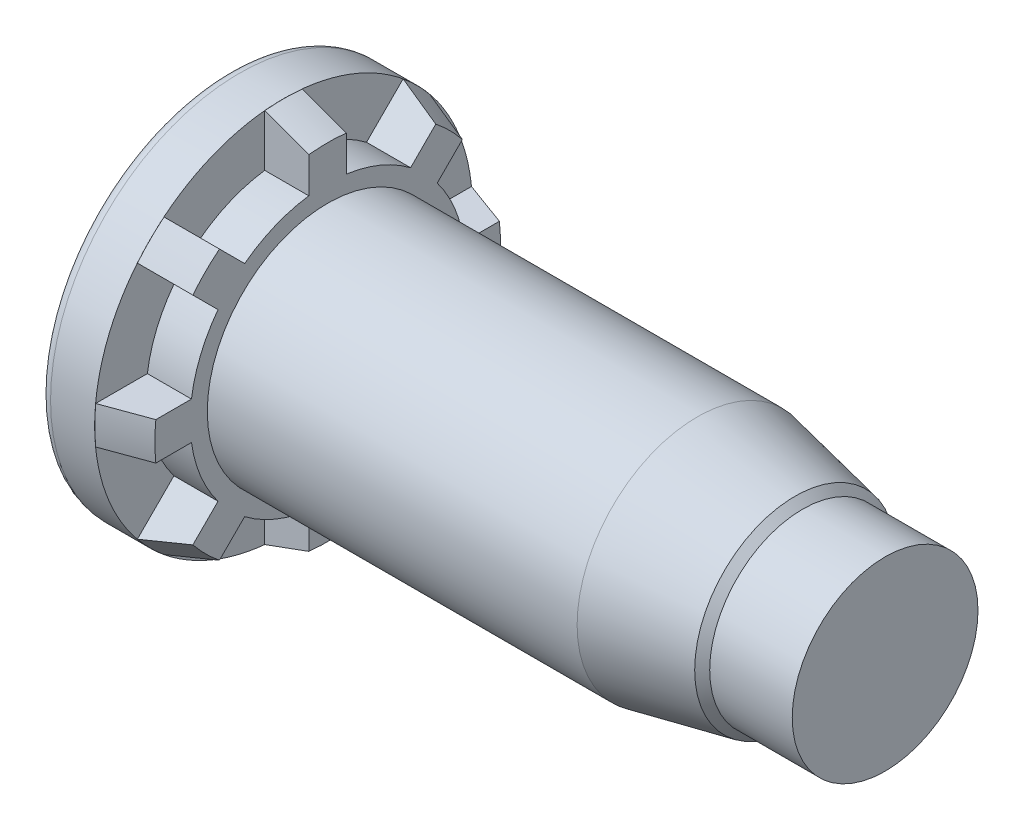
SolidWorks part; units mm, degrees
revolve "BaseBody" add sketch "BodySke" angle 360 about L6
sketch "BodySke" plane through (0, 0, 0) normal (0, 0, 1) x (1, 0, 0)
  line L0 (-2.29, 7.392) -> (-2.29, 0)
  line L1 (1.832, 7.1816) -> (1.832, 5)
  line L2 (0.0025, 7.8475) -> (1.832, 7.1816)
  line L3 (1.832, 5) -> (17.2, 5)
  line L4 (17.2, 5) -> (21.258, 4.172)
  line L5 (25, 0) -> (-2.29, 0)
  line L6 (0, 0) -> (50.554, 0) construction
  line L7 (21.57, 3.86) -> (25, 3.86)
  line L8 (21.57, 3.86) -> (21.258, 4.172)
  line L9 (-1.832, 7.85) -> (0, 7.85)
  line L10 (0.0025, 7.8475) -> (0, 7.8475)
  line L11 (1.5, 19.05) -> (1.5, -3.175) construction
  line L12 (0, 7.8475) -> (0, 7.85)
  line L13 (25, 3.86) -> (25, 0)
  arc A0 (-2.29, 7.392) -> (-1.832, 7.85) centre (-1.832, 7.392) cw
  dimension "Fillet_rad" = 0.458
  dimension "T_dim" = 2.29
  dimension "H_dia" = 15.7
  dimension "D2" = 0.0025
  dimension "D3" = 0.0025
  dimension "Advance" = 1.5
  dimension "D1" = 20
  dimension "Clinch_ht" = 1.832
  dimension "Dog_len" = 3.43
  dimension "Length" = 25
  dimension "Dog_dia" = 7.72
  dimension "D4" = 45
  dimension "Diameter" = 10
  dimension "Thread_trans" = 4.37
  dimension "Minor_dia" = 8.344
cosmetic thread "ThreadCosmetic" [suppressed] parameters "Thread_length"=17.158, "Thread_minor"=8.344
ref_plane "Plane1" through (0, 0, 0) normal (0, 0, 1) x (1, 0, 0)
ref_plane "Plane2" through (0, 0, 0) normal (0, 1, 0) x (1, 0, 0)
ref_plane "Plane3" through (0, 0, 0) normal (1, 0, 0) x (0, 0, -1)
sketch "ThdSchSke" plane through (0, 0, 0) normal (0, 0, 1) x (1, 0, 0)
  line L0 (4.1, -4.172) -> (3.5202, -5)
  line L1 (4.1, -4.172) -> (4.6798, -5)
  line L2 (4.6798, -5) -> (4.6798, -6.25)
  line L3 (-3.175, 0) -> (5.1513, 0) construction
  line L4 (0, -7.85) -> (0, 7.85) construction
  line L5 (4.6798, -6.25) -> (3.5202, -6.25)
  line L6 (3.5202, -6.25) -> (3.5202, -5)
  line L7 (22.1518, 6.5809) -> (22.1518, 1.1961) construction
  dimension "Diameter" = 10
  dimension "Thread_minor" = 8.344
  dimension "Start" = 4.1
revolve "ThreadSchematic" [suppressed] cut sketch "ThdSchSke" angle 360 about L3
pattern_linear "ThdSchPat" [suppressed]
sketch "RibCutSke" plane through (1.832, 1.7944, -0.091) normal (1, 0, 0) x (0, 0, -1)
  line L0 (0.6912, 3.8643) -> (0.6912, 6.0165)
  line L1 (3.3573, 2.76) -> (4.8791, 4.2818)
  line L2 (0.6912, 3.144) -> (0.6912, 2.4006) construction
  line L3 (-0.091, -1.7944) -> (-0.091, 5.0239) construction
  line L4 (-0.091, -1.7944) -> (0.6912, 3.144) construction
  line L5 (-0.091, -1.7944) -> (2.848, 2.2507) construction
  line L6 (2.848, 2.2507) -> (2.3273, 1.73) construction
  arc A1 (3.3573, 2.76) -> (0.6912, 3.8643) centre (-0.091, -1.7944) ccw
  arc A2 (4.8791, 4.2818) -> (0.6912, 6.0165) centre (-0.091, -1.7944) ccw
  circle A3 centre (-0.091, -1.7944) radius 7.1816 construction
  circle A4 centre (-0.091, -1.7944) radius 5 construction
  dimension "Rib_root_half_angle" = 9
  dimension "Rib_root_gap_angle" = 27
  dimension "Angle" = 45
extrude "RibCut" cut sketch "RibCutSke" against normal blind 1.832
pattern_circular "RibCutsPat" count 8 every 45 about axis through (0, 0, 0) along (1, 0, 0) of "RibCut"
equation "' \"Length@BodySke\" = 25"
equation "' \"H_dia@BodySke\" = 15.7"
equation "' \"Start@ThdSchSke\" = 4.1"
equation "' \"T_dim@BodySke\" = 2.29"
equation "' \"Dog_dia@BodySke\" = 7.72"
equation "' \"Dog_len@BodySke\" = 3.43"
equation "' \"Thread_trans@BodySke\" = 4.37"
equation "' \"Diameter@BodySke\" = 10"
equation "' \"Minor_dia@BodySke\" =  8.344"
equation "' \"Minor_dia@BodySke\" = 8.344"
equation "' \"Advance@BodySke\" = 1.5"
equation "\"Fillet_rad@BodySke\" =  \"T_dim@BodySke\" * 0.2"
equation "\"Clinch_ht@BodySke\" = \"T_dim@BodySke\" * 0.8"
equation "\"Num_ribs@RibCutsPat\" = 8"
equation "\"Angle@RibCutSke\" =\"Angle@RibCutsPat\""
equation "\"Rib_root_half_angle@RibCutSke\" = \"Angle@RibCutSke\" / 5"
equation "\"Rib_root_gap_angle@RibCutSke\" = \"Angle@RibCutSke\" - (2 * \"Rib_root_half_angle@RibCutSke\" )"
equation "\"Rib_root_dia@RibCutSke\" = \"Diameter@BodySke\""
equation "\"Inner_dia@RibCutSke\" = \"Diameter@BodySke\" + ( \"H_dia@BodySke\" - \"Diameter@BodySke\" ) / 4"
equation "\"Outer_dia@RibCutSke\" = \"H_dia@BodySke\""
equation "\"Depth@RibCut\" = \"Clinch_ht@BodySke\""
equation "\"Thread_length@ThreadCosmetic\" = \"Length@BodySke\" - \"Start@ThdSchSke\"  - \"Dog_len@BodySke\"  - ( \"Minor_dia@BodySke\" - \"Dog_dia@BodySke\" ) / 2"
equation "\"Thread_minor@ThreadCosmetic\" = \"Minor_dia@BodySke\""
equation "\"Thread_minor@ThdSchSke\" = \"Minor_dia@BodySke\""
equation "\"Diameter@ThdSchSke\" = \"Diameter@BodySke\""
equation "\"Overcut@ThdSchSke\" = \"Diameter@BodySke\" * 1.25"
equation "\"Num_threads@ThdSchPat\" = int( \"Thread_length@ThreadCosmetic\" / \"Advance@BodySke\" + 0.999 )  + 1"
equation "\"Advance@ThdSchPat\" = \"Thread_length@ThreadCosmetic\" /  (\"Num_threads@ThdSchPat\" - 1) 'relax it"
equation "\"Num_threads@ThdSchPat\" = \"Num_threads@ThdSchPat\" - sgn( \"Num_threads@ThdSchPat\" - 1) '---chamfered tips only---"
